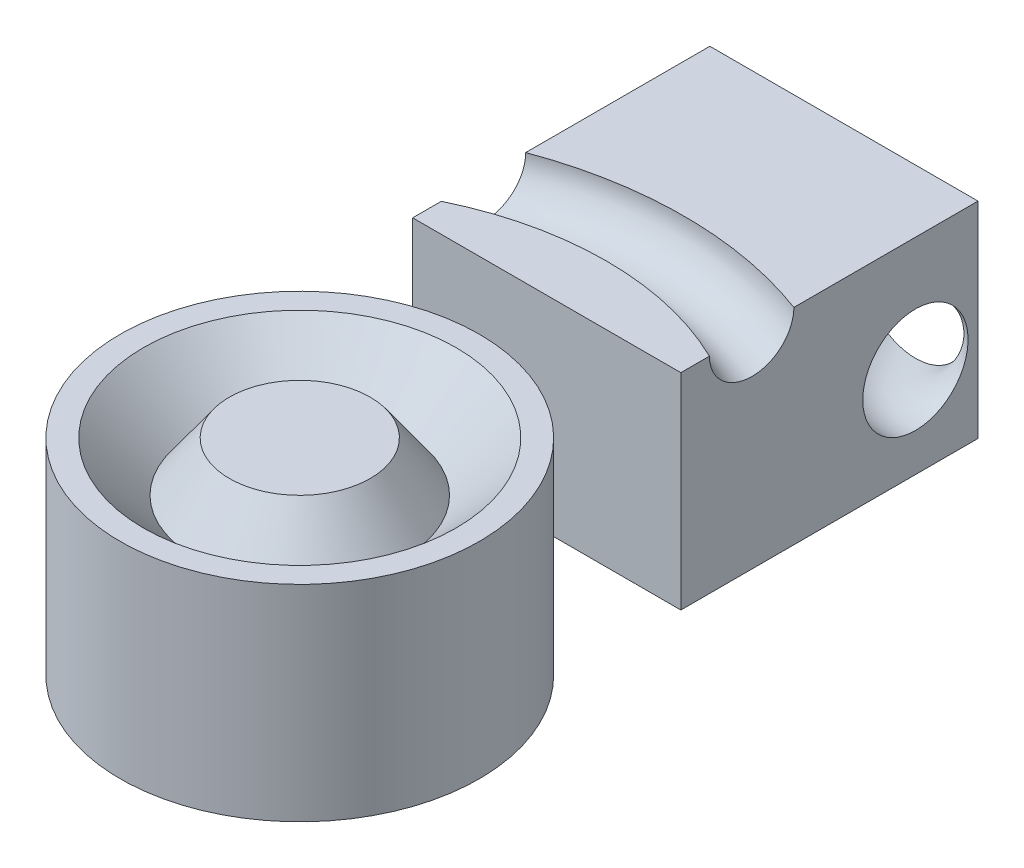
SolidWorks part; units mm, degrees
ref_plane "Front Plane" through (0, 0, 0) normal (0, 0, 1) x (1, 0, 0)
ref_plane "Top Plane" through (0, 0, 0) normal (0, 1, 0) x (1, 0, 0)
ref_plane "Right Plane" through (0, 0, 0) normal (1, 0, 0) x (0, 0, -1)
sketch "Sketch1" plane through (0, 0, 0) normal (0, 0, 1) x (1, 0, 0)
  line L1 (0, 0) -> (58.687, 0)
  line L2 (0, 0) -> (0, 67.2093)
  line L3 (0, 67.2093) -> (58.687, 67.2093)
  line L4 (58.687, 0) -> (58.687, 67.2093)
revolve "Revolve1" add sketch "Sketch1" angle 360 about L2
sketch "Sketch2" plane through (0, 0, 0) normal (0, 1, 0) x (1, 0, 0)
  line L0 (0, 0) -> (0, 80.7292) construction
  line L1 (-43.8303, 177.8668) -> (43.8303, 177.8668)
  line L2 (-43.8303, 177.8668) -> (-43.8303, 80.7292)
  line L3 (-43.8303, 80.7292) -> (43.8303, 80.7292)
  line L4 (43.8303, 177.8668) -> (43.8303, 80.7292)
extrude "Boss-Extrude1" add sketch "Sketch2" along normal up to surface (67.2093 mm away) separate body up to face at (0, 67.2093, -58.687)
sketch "Sketch3" plane through (0, 0, 0) normal (1, 0, 0) x (0, 0, -1)
  line L0 (58.687, 67.2093) -> (-58.687, 67.2093) construction
  line L1 (0, 0) -> (0, 67.2093) construction
  line L2 (23.0349, 67.2093) -> (34.6192, 50.9621)
  line L3 (34.6192, 50.9621) -> (51.0947, 67.2093)
  line L4 (51.0947, 67.2093) -> (23.0349, 67.2093)
  circle A0 centre (112.8778, 67.2093) radius 12.7
  dimension "D1" = 25.4
revolve "Cut-Revolve1" cut sketch "Sketch3" angle 360 about L1
sketch "Sketch4" plane through (43.8303, 0, 0) normal (1, 0, 0) x (0, 0, -1)
  circle A0 centre (157.4131, 29.685) radius 17.2074
revolve "Cut-Revolve2" cut sketch "Sketch4" angle 360 about axis through (43.8303, 198.053, -177.8668) along (0, -1, 0)
